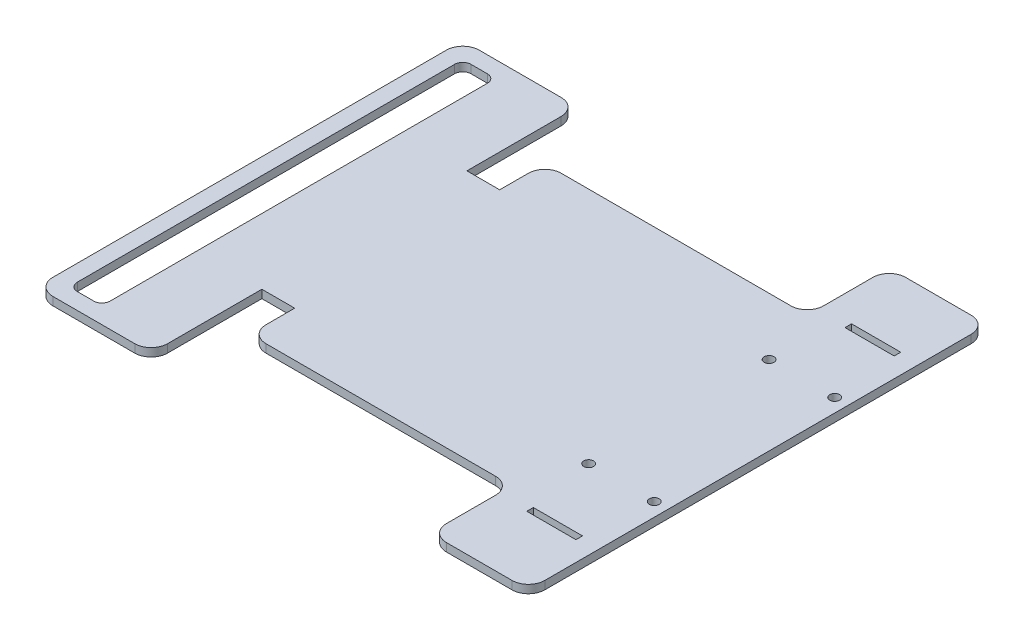
SolidWorks part; units mm, degrees
ref_plane "Front Plane" through (0, 0, 0) normal (0, 0, 1) x (1, 0, 0)
ref_plane "Top Plane" through (0, 0, 0) normal (0, 1, 0) x (1, 0, 0)
ref_plane "Right Plane" through (0, 0, 0) normal (1, 0, 0) x (0, 0, -1)
sketch "Sketch1" plane through (0, 0, 0) normal (0, 1, 0) x (1, 0, 0)
  line L0 (45.5467, 65) -> (45.5467, 49.9983)
  line L2 (-79.4533, 60) -> (-79.4533, -60)
  line L4 (75.5467, 65) -> (75.5467, -65)
  line L5 (-43.1804, 40.0101) -> (75.5467, -70) construction
  line L6 (-42.5, -38.3871) -> (38.3251, 34.6162) construction
  line L7 (-44.4533, 60) -> (-44.4533, 46.2483)
  line L8 (-29.4533, 44.9983) -> (40.5467, 44.9983)
  line L9 (-42.5, -0.0017) -> (47.5, -0.0017) construction
  line L10 (-29.4533, -45.0017) -> (40.5467, -45.0017)
  line L11 (50.5467, 70) -> (70.5467, 70)
  line L12 (50.5467, -70) -> (70.5467, -70)
  line L13 (45.5467, -50.0017) -> (45.5467, -65)
  line L14 (-44.4533, -46.2517) -> (-44.4533, -60)
  line L15 (-74.4533, 65) -> (-49.4533, 65)
  line L16 (-71.9533, 60) -> (-66.9533, 60)
  line L17 (-74.4533, 57.5) -> (-74.4533, -57.5)
  line L18 (-71.9533, -60) -> (-66.9533, -60)
  line L19 (-64.4533, 57.5) -> (-64.4533, -57.5)
  line L21 (-44.4533, 46.2483) -> (-44.4533, 31.2483)
  line L22 (-44.4533, 31.2483) -> (-34.4533, 31.2483)
  line L23 (-34.4533, 39.9983) -> (-34.4533, 31.2483)
  line L25 (-44.4533, -46.2517) -> (-44.4533, -31.2517)
  line L26 (-44.4533, -31.2517) -> (-34.4533, -31.2517)
  line L27 (-34.4533, -40.0017) -> (-34.4533, -31.2517)
  line L28 (-49.4533, -65) -> (-74.4533, -65)
  arc A0 (-29.4533, -45.0017) -> (-34.4533, -40.0017) centre (-29.4533, -40.0017) cw
  arc A1 (-29.4533, 44.9983) -> (-34.4533, 39.9983) centre (-29.4533, 39.9983) ccw
  arc A2 (40.5467, 44.9983) -> (45.5467, 49.9983) centre (40.5467, 49.9983) ccw
  arc A3 (40.5467, -45.0017) -> (45.5467, -50.0017) centre (40.5467, -50.0017) cw
  arc A4 (70.5467, -70) -> (75.5467, -65) centre (70.5467, -65) ccw
  arc A5 (45.5467, -65) -> (50.5467, -70) centre (50.5467, -65) ccw
  arc A6 (75.5467, 65) -> (70.5467, 70) centre (70.5467, 65) ccw
  arc A7 (45.5467, 65) -> (50.5467, 70) centre (50.5467, 65) cw
  arc A12 (-66.9533, -60) -> (-64.4533, -57.5) centre (-66.9533, -57.5) ccw
  arc A13 (-74.4533, -57.5) -> (-71.9533, -60) centre (-71.9533, -57.5) ccw
  arc A14 (-66.9533, 60) -> (-64.4533, 57.5) centre (-66.9533, 57.5) cw
  arc A15 (-71.9533, 60) -> (-74.4533, 57.5) centre (-71.9533, 57.5) ccw
  arc A16 (-44.4533, -60) -> (-49.4533, -65) centre (-49.4533, -60) cw
  arc A17 (-79.4533, -60) -> (-74.4533, -65) centre (-74.4533, -60) ccw
  arc A18 (-44.4533, 60) -> (-49.4533, 65) centre (-49.4533, 60) ccw
  arc A19 (-79.4533, 60) -> (-74.4533, 65) centre (-74.4533, 60) cw
  point P0 (0, 0)
  point P20 (-64.4533, 0)
  point P36 (45.5467, 44.9983)
  point P39 (45.5467, -45.0017)
  point P45 (45.5467, -70)
  point P48 (75.5467, 70)
  point P51 (45.5467, 70)
  point P60 (-79.4533, 70)
  point P65 (-74.4533, -60)
  point P68 (-64.4533, 60)
  point P71 (-74.4533, 60)
  dimension "D13" = 5
  dimension "D14" = 2.5
  dimension "D17" = 5
  dimension "D1" = 140
  dimension "D2" = 155
  dimension "D3" = 30
  dimension "D4" = 90
  dimension "D5" = 90
  dimension "D6" = 10
  dimension "D7" = 120
  dimension "D8" = 5
  dimension "D9" = 15
  dimension "D10" = 10
  dimension "D11" = 10
  dimension "D12" = 15
  dimension "D15" = 130
  dimension "D16" = 5
extrude "Boss-Extrude1" add sketch "Sketch1" along normal blind 2.5
sketch "Sketch2" plane through (0, 2.5, 0) normal (0, 1, 0) x (1, 0, 0)
  line L0 (51.4178, 27.5) -> (51.4178, -27.5) construction
  circle A0 centre (51.4178, 27.5) radius 1.5
  circle A1 centre (51.4178, -27.5) radius 1.5
  circle A2 centre (71.4178, -27.5) radius 1.5
  circle A3 centre (71.4178, 27.5) radius 1.5
  point P4 (51.4178, 0)
  dimension "D3" = 3
  dimension "D4" = 3
  dimension "D5" = 3
  dimension "D6" = 3
extrude "Cut-Extrude1" cut sketch "Sketch2" against normal through all
sketch "Sketch4" plane through (0, 0, 0) normal (0, -1, 0) x (1, 0, 0)
  line L0 (54.5467, -47.5) -> (54.5467, -49.5)
  line L1 (54.5467, 47.5) -> (69.5467, 47.5)
  line L2 (54.5467, 47.5) -> (54.5467, 49.5)
  line L3 (54.5467, 49.5) -> (69.5467, 49.5)
  line L4 (69.5467, 47.5) -> (69.5467, 49.5)
  line L5 (75.5467, 65) -> (75.5467, -65) construction
  line L6 (0, 0) -> (75.5467, 0) construction
  line L7 (69.5467, -47.5) -> (69.5467, -49.5)
  line L8 (54.5467, -49.5) -> (69.5467, -49.5)
  line L9 (54.5467, -47.5) -> (69.5467, -47.5)
  circle A0 centre (51.4178, 27.5) radius 1.5 construction
  dimension "D1" = 2
  dimension "D2" = 15
  dimension "D3" = 20
  dimension "D4" = 6
extrude "Cut-Extrude2" cut sketch "Sketch4" against normal blind 2.5
